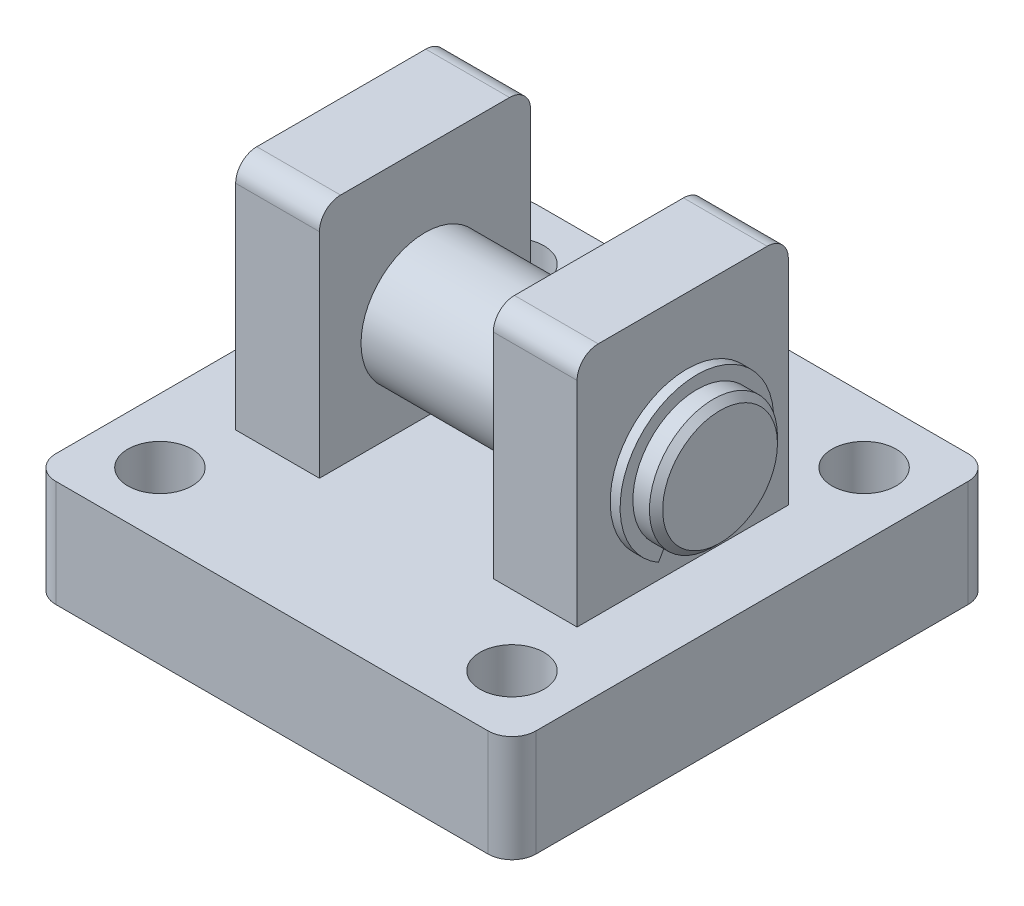
SolidWorks part; units mm, degrees
ref_plane "前视基准面" through (0, 0, 0) normal (0, 0, 1) x (1, 0, 0)
ref_plane "上视基准面" through (0, 0, 0) normal (0, 1, 0) x (1, 0, 0)
ref_plane "右视基准面" through (0, 0, 0) normal (1, 0, 0) x (0, 0, -1)
sketch "草图1" plane through (0, 0, 0) normal (0, 1, 0) x (1, 0, 0)
  line L0 (-16, 0) -> (16, 0) construction
  line L1 (22.5, -22.5) -> (-22.5, -22.5)
  line L2 (22.5, -22.5) -> (22.5, 22.5)
  line L3 (22.5, 22.5) -> (-22.5, 22.5)
  line L4 (-22.5, -22.5) -> (-22.5, 22.5)
  line L5 (22.5, -22.5) -> (-22.5, 22.5) construction
  line L6 (22.5, 22.5) -> (-22.5, -22.5) construction
  line L7 (0, 0) -> (0, 22.5) construction
  circle A0 centre (-16.5, 16.5) radius 3
  point P0 (0, 0)
  point P10 (8.15, 0)
  point P11 (-8.15, 0)
  point P12 (16.4, 0)
  point P13 (19.5, 0)
  dimension "L" = 6
  dimension "S" = 45
  dimension "CT" = 32
  dimension "CP" = 16.3
  dimension "PB1" = 32.8
  dimension "PA1" = 39
  dimension "T" = 33
sketch "草图2" plane through (0, 0, 0) normal (1, 0, 0) x (0, 0, -1)
  line L0 (0, 0) -> (0, 32) construction
  circle A0 centre (0, 19) radius 6
  point P5 (0, 10)
  dimension "CE" = 12
  dimension "CJ" = 32
  dimension "CC" = 19
  dimension "CD" = 10
sketch "草图3" plane through (0, 0, 0) normal (0, 1, 0) x (1, 0, 0)
  line L0 (-22.5, -22.5) -> (-22.5, 22.5) construction
  line L1 (22.5, -22.5) -> (-22.5, -22.5) construction
  line L2 (22.5, -22.5) -> (22.5, 22.5) construction
  line L3 (22.5, 22.5) -> (-22.5, 22.5) construction
  line L4 (-22.5, -22.5) -> (-22.5, 22.5)
  line L5 (22.5, -22.5) -> (-22.5, -22.5)
  line L6 (22.5, -22.5) -> (22.5, 22.5)
  line L7 (22.5, 22.5) -> (-22.5, 22.5)
extrude "凸台-拉伸1" add sketch "草图3" along normal up to vertex (10 mm away) up to point (0, 10, 0)
sketch "草图4" plane through (22.5, 0, 0) normal (1, 0, 0) x (0, 0, -1)
  line L0 (-9.9, 10) -> (-9.9, 32)
  line L1 (-22.5, 10) -> (22.5, 10) construction
  line L2 (-9.9, 32) -> (9.9, 32)
  line L3 (9.9, 32) -> (9.9, 10)
  line L4 (0, 10) -> (0, 19) construction
  line L5 (-9.9, 10) -> (9.9, 10)
  dimension "D1" = 19.8
extrude "凸台-拉伸2" add sketch "草图4" along normal up to vertex (-6.5 mm away) from vertex at -38.5 starting at point (-16, 0, 0)
sketch "草图5" plane through (0, 10, 0) normal (0, 1, 0) x (-1, 0, 0)
  line L0 (8.15, -9.9) -> (8.15, 9.9)
  line L1 (-8.15, -9.9) -> (-8.15, 9.9)
  line L2 (8.15, -9.9) -> (-8.15, -9.9)
  line L3 (8.15, 9.9) -> (-8.15, 9.9)
  line L5 (-16, 9.9) -> (16, 9.9) construction
  line L6 (-16, -9.9) -> (16, -9.9) construction
extrude "切除-拉伸1" cut sketch "草图5" along normal up to surface (22 mm away) up to face at (0, 32, 0)
sketch "草图6" plane through (0, 0, 0) normal (1, 0, 0) x (0, 0, -1)
  circle A0 centre (0, 19) radius 6 construction
  circle A1 centre (0, 19) radius 6
extrude "凸台-拉伸3" add sketch "草图6" along normal up to vertex (19.5 mm away) up to point (19.5, 0, 0)
mirror "镜向1" about plane through (0, 0, 0) normal (1, 0, 0) of "凸台-拉伸3"
sketch "草图7" plane through (19.5, 0, 0) normal (1, 0, 0) x (0, 0, -1)
  circle A0 centre (0, 19) radius 5.4
  circle A1 centre (0, 19) radius 6 construction
  circle A2 centre (0, 19) radius 6
  dimension "D1" = 10.8
extrude "切除-拉伸3" cut sketch "草图7" along normal blind 0.93 from vertex at -3.1 starting at point (16.4, 0, 0)
mirror "镜向2" about plane through (0, 0, 0) normal (1, 0, 0) of "切除-拉伸3"
sketch "草图8" plane through (0, 10, 0) normal (0, 1, 0) x (1, 0, 0)
  circle A0 centre (-16.5, 16.5) radius 3 construction
  circle A1 centre (-16.5, 16.5) radius 3
extrude "切除-拉伸4" cut sketch "草图8" against normal through all
mirror "镜向3" about plane through (0, 0, 0) normal (1, 0, 0) of "切除-拉伸4"
mirror "镜向4" about plane through (0, 0, 0) normal (0, 0, 1) of "镜向3", "切除-拉伸4"
sketch "草图9" plane through (16.4, 0, 0) normal (1, 0, 0) x (0, 0, -1)
  line L0 (0, 19) -> (-3.6, 12.7646)
  line L1 (0, 0) -> (0, 32) construction
  line L2 (0, 19) -> (3.6, 12.7646)
  arc A0 (3.6, 12.7646) -> (-3.6, 12.7646) centre (0, 19) ccw
  dimension "D1" = 14.4
  dimension "D2" = 30
  dimension "D3" = 30
extrude "凸台-拉伸4" add sketch "草图9" along normal up to surface (0.93 mm away) up to face at (17.33, 19, -6)
mirror "镜向5" about plane through (0, 0, 0) normal (1, 0, 0) of "凸台-拉伸4"
fillet "圆角1" radius 2.25 4 edges at (22.5, 5, -22.5) (-22.5, 5, -22.5) (-22.5, 5, 22.5) (22.5, 5, 22.5)
fillet "圆角2" radius 1.98 4 edges at (-12.075, 32, 9.9) (-12.075, 32, -9.9) (12.075, 32, 9.9) (12.075, 32, -9.9)
chamfer "倒角1" distance 0.62 angle 45 2 edges at (-19.5, 19, -6) (19.5, 19, -6)
equation "\"D1@草图4\" = \"T@草图1\"*0.6"
equation "\"D1@草图7\" = \"CE@草图2\"*0.9"
equation "\"D1@切除-拉伸3\" = (  \"PA1@草图1\"-\"PB1@草图1\" ) /2*0.3"
equation "\"D1@草图9\" = \"CE@草图2\"*1.2"
equation "\"D1@圆角1\" = \"S@草图1\"*0.05"
equation "\"D1@圆角2\" = \"D1@草图4\"*0.1"
equation "\"D1@倒角1\" = \"CE@草图2\"/100+0.5"
